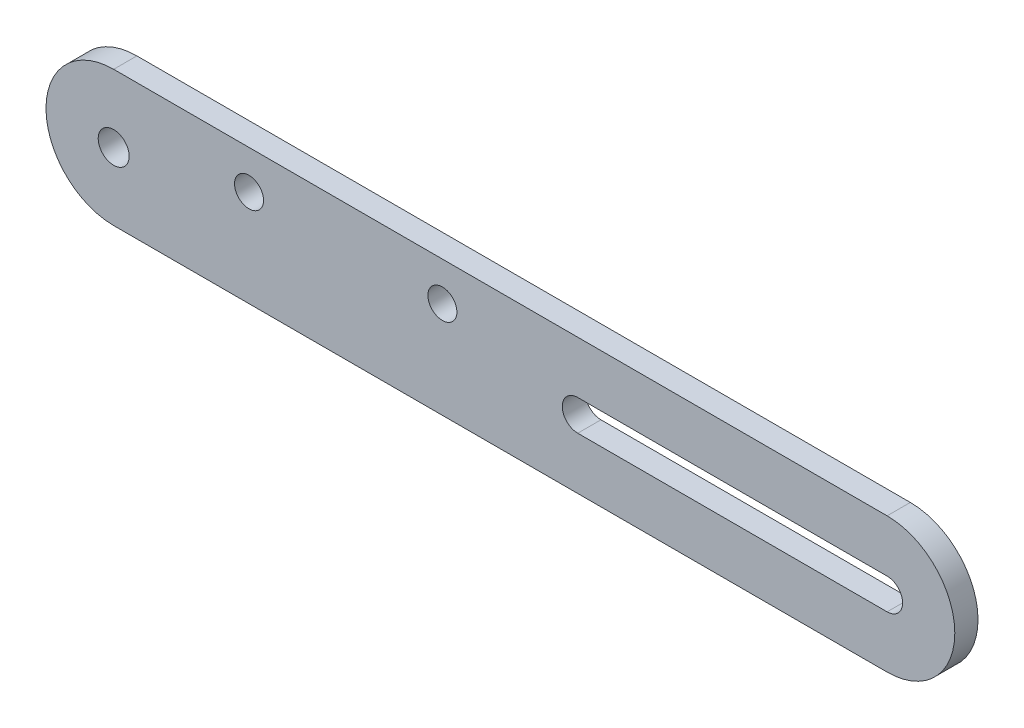
SolidWorks part; units mm, degrees
ref_plane "Plan de face" through (0, 0, 0) normal (0, 0, 1) x (1, 0, 0)
ref_plane "Plan de dessus" through (0, 0, 0) normal (0, 1, 0) x (1, 0, 0)
ref_plane "Plan de droite" through (0, 0, 0) normal (1, 0, 0) x (0, 0, -1)
sketch "Esquisse1" plane through (0, 0, 0) normal (0, 0, 1) x (1, 0, 0)
  line L0 (-111.2865, 0) -> (88.7135, 0) construction
  line L1 (-111.2865, 17.5) -> (88.7135, 17.5)
  line L2 (-111.2865, -17.5) -> (88.7135, -17.5)
  line L3 (88.7135, 0) -> (8.7135, 0) construction
  line L4 (88.7135, -4) -> (8.7135, -4)
  line L5 (88.7135, 4) -> (8.7135, 4)
  arc A0 (-111.2865, 17.5) -> (-111.2865, -17.5) centre (-111.2865, 0) ccw
  arc A1 (88.7135, -17.5) -> (88.7135, 17.5) centre (88.7135, 0) ccw
  circle A2 centre (-111.2865, 0) radius 4
  arc A4 (88.7135, -4) -> (88.7135, 4) centre (88.7135, 0) ccw
  arc A5 (8.7135, 4) -> (8.7135, -4) centre (8.7135, 0) ccw
  point P3 (-11.2865, 0)
  point P12 (48.7135, 0)
  dimension "D3" = 8
  dimension "D1" = 35
  dimension "D2" = 200
  dimension "D4" = 8
  dimension "D5" = 80
extrude "Boss.-Extru.1" add sketch "Esquisse1" along normal blind 6
sketch "Esquisse2" plane through (0, 0, 6) normal (0, 0, 1) x (1, 0, 0)
  line L0 (88.7135, 17.5) -> (-111.2865, 17.5) construction
  circle A0 centre (-76.2865, 7.5) radius 3.75
  circle A1 centre (-26.2865, 7.5) radius 3.75
  circle A2 centre (-111.2865, 0) radius 4 construction
  dimension "D1" = 7.5
  dimension "D2" = 10
  dimension "D3" = 10
  dimension "D4" = 50
  dimension "D5" = 35
extrude "Enlèv. mat.-Extru.1" cut sketch "Esquisse2" against normal up to next
